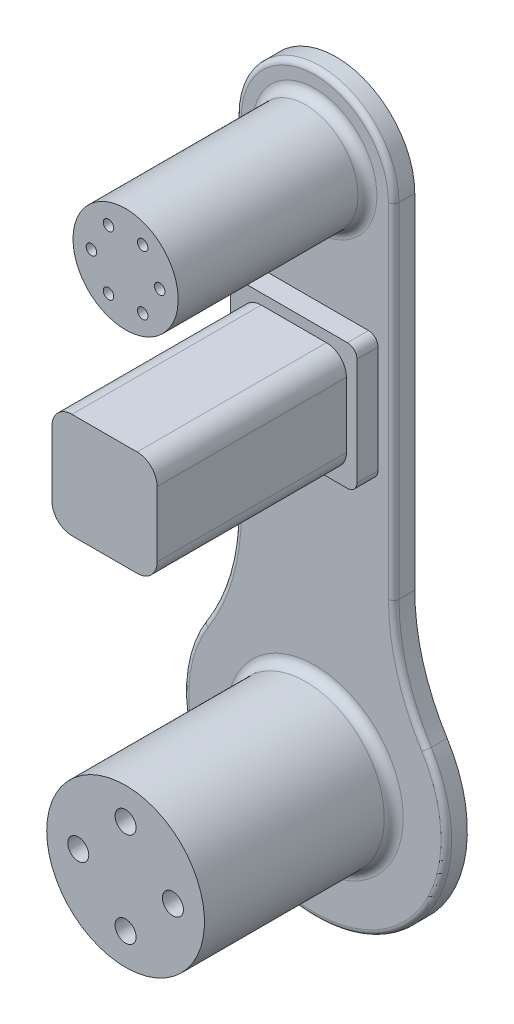
SolidWorks part; units mm, degrees
ref_plane "Front Plane" through (0, 0, 0) normal (0, 0, 1) x (1, 0, 0)
ref_plane "Top Plane" through (0, 0, 0) normal (0, 1, 0) x (1, 0, 0)
ref_plane "Right Plane" through (0, 0, 0) normal (1, 0, 0) x (0, 0, -1)
sketch "Sketch1" plane through (0, 0, 0) normal (0, 0, 1) x (1, 0, 0)
  line L0 (0, -250) -> (0, 250) construction
  circle A0 centre (0, 250) radius 50
  circle A1 centre (0, -250) radius 75
  point P4 (0, 0)
  dimension "D1" = 100
  dimension "150" = 150
  dimension "D2" = 500
extrude "Boss-Extrude1" add sketch "Sketch1" along normal mid plane 180
sketch "Sketch2" plane through (0, 0, 90) normal (0, 0, 1) x (1, 0, 0)
  circle A0 centre (0, -250) radius 45 construction
  circle A1 centre (-45, -250) radius 10
  circle A2 centre (0, -250) radius 45 construction
  circle A3 centre (0, -205) radius 10
  circle A4 centre (0, -250) radius 45 construction
  circle A5 centre (45, -250) radius 10
  circle A6 centre (0, -250) radius 45 construction
  circle A7 centre (0, -295) radius 10
  circle A8 centre (0, 250) radius 32.5 construction
  circle A9 centre (-32.5, 250) radius 5
  circle A10 centre (-16.25, 278.1458) radius 5
  circle A11 centre (0, 250) radius 32.5 construction
  circle A12 centre (16.25, 278.1458) radius 5
  circle A13 centre (0, 250) radius 32.5 construction
  circle A14 centre (32.5, 250) radius 5
  circle A15 centre (0, 250) radius 32.5 construction
  circle A16 centre (16.25, 221.8542) radius 5
  circle A17 centre (0, 250) radius 32.5 construction
  circle A18 centre (-16.25, 221.8542) radius 5
  circle A19 centre (0, 250) radius 32.5 construction
  point P17 (0, -250)
  point P38 (0, 250)
  dimension "D1" = 90
  dimension "D2" = 20
  dimension "D4" = 65
  dimension "D5" = 10
  dimension "D3" = 4
  dimension "D6" = 6
extrude "Cut-Extrude1" cut sketch "Sketch2" against normal blind 40
sketch "Sketch3" plane through (0, 0, -90) normal (0, 0, -1) x (-1, 0, 0)
  line L0 (-75, 250) -> (-75, -76.7949)
  line L1 (0, 250) -> (0, 0) construction
  line L2 (75, 250) -> (75, -76.7949)
  arc A0 (75, 250) -> (-75, 250) centre (0, 250) ccw
  arc A1 (-105.7692, -183.3827) -> (105.7692, -183.3827) centre (0, -250) ccw
  arc A2 (-75, -76.7949) -> (-105.7692, -183.3827) centre (-275, -76.7949) cw
  arc A3 (75, -76.7949) -> (105.7692, -183.3827) centre (275, -76.7949) ccw
  point P1 (0, 0)
  point P4 (0, 0)
  point P16 (0, 0)
  dimension "D1" = 150
  dimension "D2" = 250
  dimension "D3" = 200
extrude "Boss-Extrude2" add sketch "Sketch3" along normal blind 20
sketch "Sketch4" plane through (0, 0, -110) normal (0, 0, -1) x (-1, 0, 0)
  line L4 (-55, 250) -> (-55, -76.7949)
  line L5 (55, -76.7949) -> (55, 250)
  line L6 (-55, 250) -> (-55, -76.7949)
  line L7 (55, -76.7949) -> (55, 250)
  arc A8 (55, 250) -> (-55, 250) centre (0, 250) ccw
  arc A9 (-88.8462, -194.0414) -> (-55, -76.7949) centre (-275, -76.7949) ccw
  arc A10 (-88.8462, -194.0414) -> (88.8462, -194.0414) centre (0, -250) ccw
  arc A11 (55, -76.7949) -> (88.8462, -194.0414) centre (275, -76.7949) ccw
  arc A12 (55, 250) -> (-55, 250) centre (0, 250) ccw
  arc A13 (-88.8462, -194.0414) -> (-55, -76.7949) centre (-275, -76.7949) ccw
  arc A14 (-88.8462, -194.0414) -> (88.8462, -194.0414) centre (0, -250) ccw
  arc A15 (55, -76.7949) -> (88.8462, -194.0414) centre (275, -76.7949) ccw
  dimension "D1" = 20
extrude "Boss-Extrude3" add sketch "Sketch4" along normal blind 20
fillet "Fillet1" radius 19 6 edges at (0, 305, -130) (-55, 86.6025, -130) (-63.6308, -137.8119, -130) (0, -355, -130) (63.6308, -137.8119, -130) (55, 86.6025, -130)
sketch "Sketch5" plane through (0, 0, -90) normal (0, 0, 1) x (1, 0, 0)
  line L0 (0, 75) -> (0, 0) construction
  line L2 (-60, 15) -> (60, 15)
  line L3 (-60, 15) -> (-60, 135)
  line L4 (-60, 135) -> (60, 135)
  line L5 (60, 15) -> (60, 135)
  line L6 (-60, 15) -> (60, 135) construction
  line L7 (-60, 135) -> (60, 15) construction
  circle A0 centre (0, 250) radius 50 construction
  dimension "D1" = 120
  dimension "D2" = 120
  dimension "D3" = 115
extrude "Boss-Extrude4" add sketch "Sketch5" along normal blind 20
sketch "Sketch6" plane through (0, 0, -70) normal (0, 0, 1) x (1, 0, 0)
  line L8 (50, 25) -> (50, 125)
  line L9 (50, 125) -> (-50, 125)
  line L10 (-50, 125) -> (-50, 25)
  line L11 (-50, 25) -> (50, 25)
  line L12 (50, 25) -> (50, 125)
  line L13 (50, 125) -> (-50, 125)
  line L14 (-50, 125) -> (-50, 25)
  line L15 (-50, 25) -> (50, 25)
  dimension "D1" = 10
extrude "Boss-Extrude5" add sketch "Sketch6" along normal blind 180
fillet "Fillet2" radius 19 4 edges at (-50, 125, 20) (-50, 25, 20) (50, 25, 20) (50, 125, 20)
fillet "Fillet3" radius 9 6 edges at (-75, -250, -90) (50, 250, -90) (-60, 15, -80) (-60, 135, -80) (60, 15, -80) (60, 135, -80)
fillet "Fillet4" radius 5 6 edges at (0, 325, -90) (-75, 86.6025, -90) (-82.8462, -132.2649, -90) (0, -375, -90) (82.8462, -132.2649, -90) (75, 86.6025, -90)
